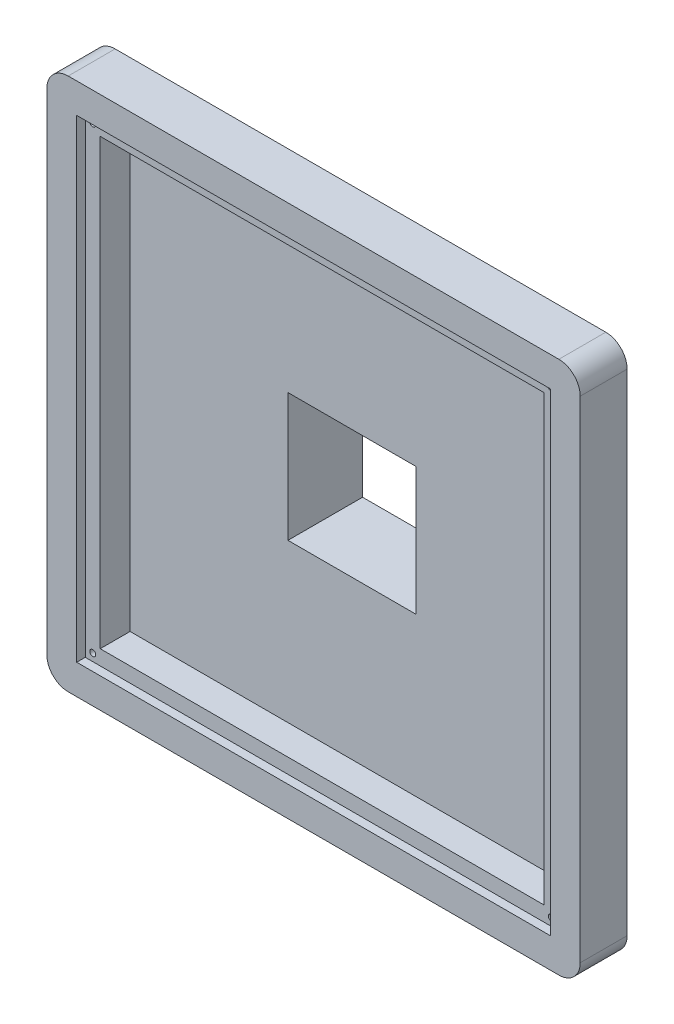
SolidWorks part; units mm, degrees
material "Polyester Resin"
ref_plane "Front Plane" through (0, 0, 0) normal (0, 0, 1) x (1, 0, 0)
ref_plane "Top Plane" through (0, 0, 0) normal (0, 1, 0) x (1, 0, 0)
ref_plane "Right Plane" through (0, 0, 0) normal (1, 0, 0) x (0, 0, -1)
sketch "Sketch1" plane through (0, 0, 0) normal (0, 0, 1) x (1, 0, 0)
  line L1 (-25.2326, 18.9253) -> (-88.2326, 18.9253)
  line L2 (-25.2326, 18.9253) -> (-25.2326, -44.0747)
  line L3 (-25.2326, -44.0747) -> (-88.2326, -44.0747)
  line L4 (-88.2326, 18.9253) -> (-88.2326, -44.0747)
  dimension "D1" = 63
  dimension "D2" = 63
extrude "Boss-Extrude1" add sketch "Sketch1" along normal blind 5
sketch "Sketch3" plane through (0, 0, 5) normal (0, 0, 1) x (1, 0, 0)
  line L4 (-88.2326, 18.9253) -> (-25.2326, 18.9253)
  line L5 (-88.2326, 18.9253) -> (-88.2326, -44.0747)
  line L6 (-88.2326, -44.0747) -> (-25.2326, -44.0747)
  line L7 (-25.2326, 18.9253) -> (-25.2326, -44.0747)
  line L8 (-88.2326, 18.9253) -> (-25.2326, -44.0747) construction
  line L9 (-88.2326, -44.0747) -> (-25.2326, 18.9253) construction
  line L10 (-86.7326, 17.4253) -> (-26.7326, 17.4253)
  line L11 (-86.7326, 17.4253) -> (-86.7326, -42.5747)
  line L12 (-86.7326, -42.5747) -> (-26.7326, -42.5747)
  line L13 (-26.7326, 17.4253) -> (-26.7326, -42.5747)
  line L14 (-86.7326, 17.4253) -> (-26.7326, -42.5747) construction
  line L15 (-86.7326, -42.5747) -> (-26.7326, 17.4253) construction
  point P6 (-56.7326, -12.5747)
  point P12 (-56.7326, -12.5747)
  dimension "D1" = 60
  dimension "D2" = 63
extrude "Boss-Extrude2" add sketch "Sketch3" along normal blind 16
sketch "Sketch7" plane through (0, 0, 21) normal (0, 0, 1) x (1, 0, 0)
  line L4 (-26.7326, -42.5747) -> (-86.7326, -42.5747)
  line L5 (-26.7326, -42.5747) -> (-26.7326, 17.4253)
  line L6 (-26.7326, 17.4253) -> (-86.7326, 17.4253)
  line L7 (-86.7326, -42.5747) -> (-86.7326, 17.4253)
  line L8 (-26.7326, -42.5747) -> (-86.7326, 17.4253) construction
  line L9 (-26.7326, 17.4253) -> (-86.7326, -42.5747) construction
  line L10 (68.2674, -137.5747) -> (-181.7326, -137.5747)
  line L11 (68.2674, -137.5747) -> (68.2674, 112.4253)
  line L12 (68.2674, 112.4253) -> (-181.7326, 112.4253)
  line L13 (-181.7326, -137.5747) -> (-181.7326, 112.4253)
  line L14 (68.2674, -137.5747) -> (-181.7326, 112.4253) construction
  line L15 (68.2674, 112.4253) -> (-181.7326, -137.5747) construction
  point P6 (-56.7326, -12.5747)
  point P12 (-56.7326, -12.5747)
  dimension "D1" = 250
  dimension "D2" = 250
extrude "Boss-Extrude5" add sketch "Sketch7" along normal blind 4
sketch "Sketch9" plane through (0, 0, 25) normal (0, 0, 1) x (1, 0, 0)
  line L4 (68.2674, -137.5747) -> (-181.7326, -137.5747)
  line L5 (68.2674, -137.5747) -> (68.2674, 112.4253)
  line L6 (68.2674, 112.4253) -> (-181.7326, 112.4253)
  line L7 (-181.7326, -137.5747) -> (-181.7326, 112.4253)
  line L8 (68.2674, -137.5747) -> (-181.7326, 112.4253) construction
  line L9 (68.2674, 112.4253) -> (-181.7326, -137.5747) construction
  line L10 (48.2674, -117.5747) -> (-161.7326, -117.5747)
  line L11 (48.2674, -117.5747) -> (48.2674, 92.4253)
  line L12 (48.2674, 92.4253) -> (-161.7326, 92.4253)
  line L13 (-161.7326, -117.5747) -> (-161.7326, 92.4253)
  line L14 (48.2674, -117.5747) -> (-161.7326, 92.4253) construction
  line L15 (48.2674, 92.4253) -> (-161.7326, -117.5747) construction
  point P6 (-56.7326, -12.5747)
  point P13 (-56.7326, -12.5747)
  dimension "D1" = 210
  dimension "D2" = 210
extrude "Boss-Extrude6" add sketch "Sketch9" along normal blind 18
sketch "Sketch10" plane through (0, 0, 43) normal (0, 0, 1) x (1, 0, 0)
  line L0 (-56.7326, -137.5747) -> (-56.7326, 112.4253)
  line L1 (-181.7326, -137.5747) -> (68.2674, -137.5747) construction
  line L2 (68.2674, 112.4253) -> (-181.7326, 112.4253) construction
  line L4 (54.2674, -123.5747) -> (-167.7326, -123.5747)
  line L5 (54.2674, -123.5747) -> (54.2674, 98.4253)
  line L6 (54.2674, 98.4253) -> (-167.7326, 98.4253)
  line L7 (-167.7326, -123.5747) -> (-167.7326, 98.4253)
  line L8 (54.2674, -123.5747) -> (-167.7326, 98.4253) construction
  line L9 (54.2674, 98.4253) -> (-167.7326, -123.5747) construction
  line L10 (-161.7326, -117.5747) -> (48.2674, -117.5747) construction
  point P6 (-56.7326, -12.5747)
  dimension "D1" = 222
  dimension "D2" = 222
extrude "Cut-Extrude1" cut sketch "Sketch10" against normal blind 4 contours L5 L6 L7 L4
sketch "Sketch14" plane through (0, 0, 25) normal (0, 0, 1) x (1, 0, 0)
  line L5 (47.2674, -116.5747) -> (-160.7326, -116.5747)
  line L6 (47.2674, -116.5747) -> (47.2674, 91.4253)
  line L7 (47.2674, 91.4253) -> (-160.7326, 91.4253)
  line L8 (-160.7326, -116.5747) -> (-160.7326, 91.4253)
  line L9 (47.2674, -116.5747) -> (-160.7326, 91.4253) construction
  line L10 (47.2674, 91.4253) -> (-160.7326, -116.5747) construction
  line L11 (-161.7326, 92.4253) -> (48.2674, 92.4253)
  line L12 (-161.7326, 92.4253) -> (-161.7326, -117.5747)
  line L13 (-161.7326, -117.5747) -> (48.2674, -117.5747)
  line L14 (48.2674, 92.4253) -> (48.2674, -117.5747)
  line L15 (-161.7326, 92.4253) -> (48.2674, -117.5747) construction
  line L16 (-161.7326, -117.5747) -> (48.2674, 92.4253) construction
  point P8 (-56.7326, -12.5747)
  point P13 (-56.7326, -12.5747)
  dimension "D1" = 208
  dimension "D2" = 208
  dimension "D3" = 210
  dimension "D4" = 210
extrude "Boss-Extrude9" add sketch "Sketch14" along normal blind 14
sketch "Sketch16" plane through (0, 0, 39) normal (0, 0, 1) x (1, 0, 0)
  line L0 (54.2674, -123.5747) -> (-167.7326, -123.5747) construction
  line L1 (54.2674, -123.5747) -> (54.2674, 98.4253) construction
  circle A0 centre (50.7674, -120.0747) radius 1.4
  dimension "D1" = 2.8
  dimension "D2" = 3.5
  dimension "D3" = 3.5
extrude "Cut-Extrude2" cut sketch "Sketch16" against normal blind 10
ref_plane "Plane26" through (-56.7326, 0, 0) normal (1, 0, 0) x (0, 0, -1)
mirror "Mirror1" about plane through (-56.7326, 0, 0) normal (1, 0, 0) of "Cut-Extrude2"
ref_plane "Plane27" through (0, -12.5747, 0) normal (0, 1, 0) x (1, 0, 0)
mirror "Mirror2" about plane through (0, -12.5747, 0) normal (0, 1, 0) of "Mirror1", "Cut-Extrude2"
fillet "Fillet1" radius 10 1 edges at (-181.7326, 112.4253, 32)
fillet "Fillet2" radius 10 1 edges at (-181.7326, -137.5747, 32)
fillet "Fillet3" radius 10 1 edges at (68.2674, 112.4253, 32)
fillet "Fillet4" radius 10 1 edges at (68.2674, -137.5747, 32)
sketch "Sketch17" plane through (0, 0, 0) normal (0, 0, -1) x (-1, 0, 0)
  line L1 (88.2326, -44.0747) -> (25.2326, -44.0747)
  line L2 (88.2326, -44.0747) -> (88.2326, 18.9253)
  line L3 (88.2326, 18.9253) -> (25.2326, 18.9253)
  line L4 (25.2326, -44.0747) -> (25.2326, 18.9253)
extrude "Boss-Extrude10" add sketch "Sketch17" along normal blind 10
sketch "Sketch18" plane through (0, 0, -10) normal (0, 0, -1) x (-1, 0, 0)
  line L0 (56.7326, 18.9253) -> (56.7326, -44.0747)
  line L1 (88.2326, 18.9253) -> (25.2326, 18.9253) construction
  line L2 (25.2326, -44.0747) -> (88.2326, -44.0747) construction
  line L4 (25.2326, 18.9253) -> (88.2326, 18.9253)
  line L5 (25.2326, 18.9253) -> (25.2326, -44.0747)
  line L6 (25.2326, -44.0747) -> (88.2326, -44.0747)
  line L7 (88.2326, 18.9253) -> (88.2326, -44.0747)
  line L8 (25.2326, 18.9253) -> (88.2326, -44.0747) construction
  line L9 (25.2326, -44.0747) -> (88.2326, 18.9253) construction
  line L10 (22.2326, 21.9253) -> (91.2326, 21.9253)
  line L11 (22.2326, 21.9253) -> (22.2326, -47.0747)
  line L12 (22.2326, -47.0747) -> (91.2326, -47.0747)
  line L13 (91.2326, 21.9253) -> (91.2326, -47.0747)
  line L14 (22.2326, 21.9253) -> (91.2326, -47.0747) construction
  line L15 (22.2326, -47.0747) -> (91.2326, 21.9253) construction
  point P6 (56.7326, -12.5747)
  point P13 (56.7326, -12.5747)
  line M4 (88.2326, -44.0747) -> (88.2326, 18.9253)
  line M5 (88.2326, 18.9253) -> (25.2326, 18.9253)
  line M6 (25.2326, 18.9253) -> (25.2326, -44.0747)
  line M7 (25.2326, -44.0747) -> (88.2326, -44.0747)
  dimension "D1" = 69
  dimension "D2" = 69
extrude "Boss-Extrude13" add sketch "Sketch18" against normal through all contours L13 L10 L11 L12 M4 M7 M6 M5
sketch "Sketch20" plane through (0, 0, 43) normal (0, 0, 1) x (1, 0, 0)
  line L0 (-22.2326, -47.0747) -> (-91.2326, -47.0747) construction
  line L1 (-22.2326, 21.9253) -> (-91.2326, 21.9253)
  line L2 (-22.2326, 21.9253) -> (-22.2326, -47.0747)
  line L3 (-22.2326, -47.0747) -> (-91.2326, -47.0747)
  line L4 (-91.2326, 21.9253) -> (-91.2326, -47.0747)
extrude "Cut-Extrude3" cut sketch "Sketch20" against normal blind 18
sketch "Sketch21" plane through (0, 0, 5) normal (0, 0, 1) x (1, 0, 0)
  line L1 (-86.7326, -42.5747) -> (-26.7326, -42.5747)
  line L2 (-86.7326, -42.5747) -> (-86.7326, 17.4253)
  line L3 (-86.7326, 17.4253) -> (-26.7326, 17.4253)
  line L4 (-26.7326, -42.5747) -> (-26.7326, 17.4253)
extrude "Cut-Extrude4" cut sketch "Sketch21" against normal through all
sketch "Sketch24" plane through (0, 0, 21) normal (0, 0, -1) x (-1, 0, 0)
  line L4 (94.7326, 25.4253) -> (18.7326, 25.4253)
  line L5 (94.7326, 25.4253) -> (94.7326, -50.5747)
  line L6 (94.7326, -50.5747) -> (18.7326, -50.5747)
  line L7 (18.7326, 25.4253) -> (18.7326, -50.5747)
  line L8 (94.7326, 25.4253) -> (18.7326, -50.5747) construction
  line L9 (94.7326, -50.5747) -> (18.7326, 25.4253) construction
  line L11 (91.2326, -47.0747) -> (22.2326, -47.0747)
  line L12 (91.2326, -47.0747) -> (91.2326, 21.9253)
  line L13 (91.2326, 21.9253) -> (22.2326, 21.9253)
  line L14 (22.2326, -47.0747) -> (22.2326, 21.9253)
  line L15 (91.2326, -47.0747) -> (22.2326, 21.9253) construction
  line L16 (91.2326, 21.9253) -> (22.2326, -47.0747) construction
  point P6 (56.7326, -12.5747)
  point P11 (56.7326, -12.5747)
  dimension "D1" = 76
  dimension "D2" = 76
extrude "Boss-Extrude14" add sketch "Sketch24" along normal blind 31
sketch "Sketch25" plane through (0, 0, -10) normal (0, 0, -1) x (-1, 0, 0)
  line L0 (94.7326, -50.5747) -> (94.7326, 25.4253) construction
  line L1 (94.7326, 25.4253) -> (18.7326, 25.4253) construction
  circle A0 centre (90.2326, 20.9253) radius 1.4
  dimension "D1" = 2.8
  dimension "D2" = 4.5
  dimension "D3" = 4.5
extrude "Cut-Extrude5" cut sketch "Sketch25" against normal blind 10
ref_plane "Plane44" through (0, -12.5747, 0) normal (0, 1, 0) x (1, 0, 0)
mirror "Mirror3" about plane through (0, -12.5747, 0) normal (0, 1, 0) of "Cut-Extrude5"
ref_plane "Plane45" through (-56.7326, 0, 0) normal (-1, 0, 0) x (0, 0, 1)
mirror "Mirror4" about plane through (-56.7326, 0, 0) normal (-1, 0, 0) of "Mirror3", "Cut-Extrude5"
